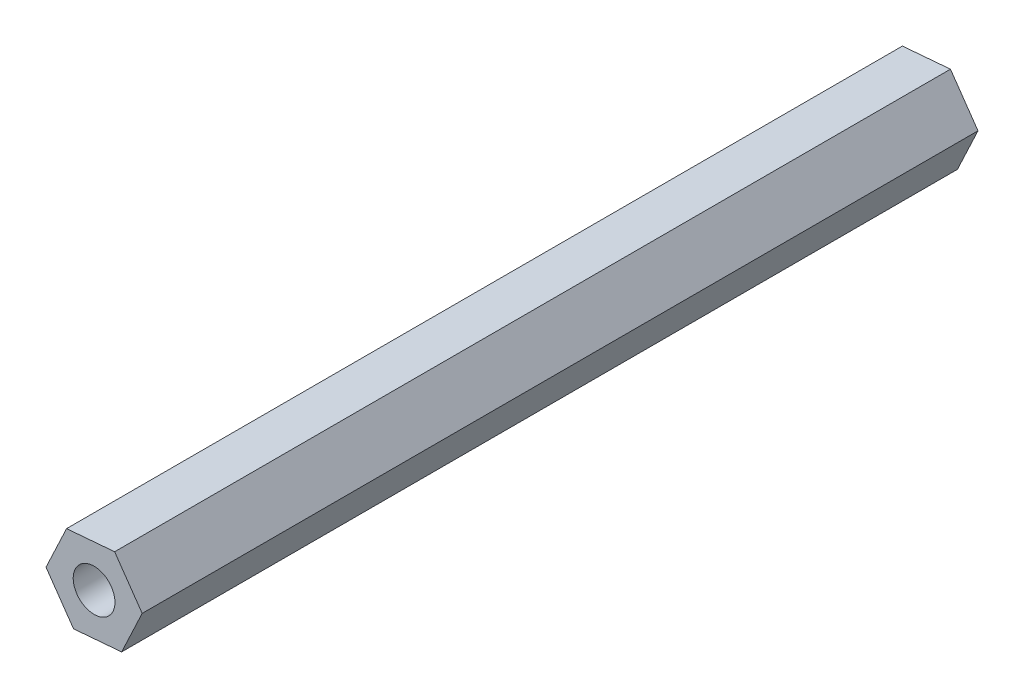
SolidWorks part; units mm, degrees
ref_plane "前视基准面" through (0, 0, 0) normal (0, 0, 1) x (1, 0, 0)
ref_plane "上视基准面" through (0, 0, 0) normal (0, 1, 0) x (1, 0, 0)
ref_plane "右视基准面" through (0, 0, 0) normal (1, 0, 0) x (0, 0, -1)
sketch "草图1" plane through (0, 0, 0) normal (0, 0, 1) x (1, 0, 0)
  line L1 (1.6473, -2.3706) -> (2.8766, 0.2414)
  line L2 (2.8766, 0.2414) -> (1.2293, 2.6119)
  line L3 (1.2293, 2.6119) -> (-1.6473, 2.3706)
  line L4 (-1.6473, 2.3706) -> (-2.8766, -0.2414)
  line L5 (-2.8766, -0.2414) -> (-1.2293, -2.6119)
  line L6 (-1.2293, -2.6119) -> (1.6473, -2.3706)
  circle A0 centre (0, 0) radius 1.5
  circle A1 centre (0, 0) radius 2.5 construction
  dimension "D1" = 3
  dimension "D2" = 5
extrude "凸台-拉伸1" add sketch "草图1" along normal blind 50 contours L5 L6 L1 L2 L3 L4 A0
hole_wizard "M3 螺纹孔1" positions "3D草图1" profile "草图2" tap size "M3" standard "GB" end condition through all
sketch3d "3D草图1"
  point P0 (0, 0, 0)
  point P3 (0, 0, 0)
  point P5 (0, 0, 0)
  point P7 (0, 0, 0)
  point P9 (0, 0, 0)
cosmetic thread "孔螺蚊线1" parameters "D2"=3
cosmetic thread "孔螺蚊线2" parameters "D2"=3
cosmetic thread "孔螺蚊线3" parameters "D2"=3
cosmetic thread "孔螺蚊线4" parameters "D2"=3
cosmetic thread "孔螺蚊线5" parameters "D2"=3
sketch "草图2" plane through (0, 0, 0) normal (1, 0, 0) x (0, 1, 0)
  line L0 (0, 0) -> (0, 50)
  line L1 (0, 50) -> (1.25, 50)
  line L2 (1.25, 50) -> (1.25, 0)
  line L5 (1.25, 0) -> (0, 0)
  line L11 (0, -6.35) -> (0, 107.95) construction
  dimension "通孔螺纹孔钻头直径" = 2.5
  dimension "通孔螺纹孔钻头深度" = 50
sketch "草图3" plane through (0, 0, 50) normal (0, 0, 1) x (1, 0, 0)
  circle A0 centre (0, 0) radius 1.5
  dimension "D1" = 3
